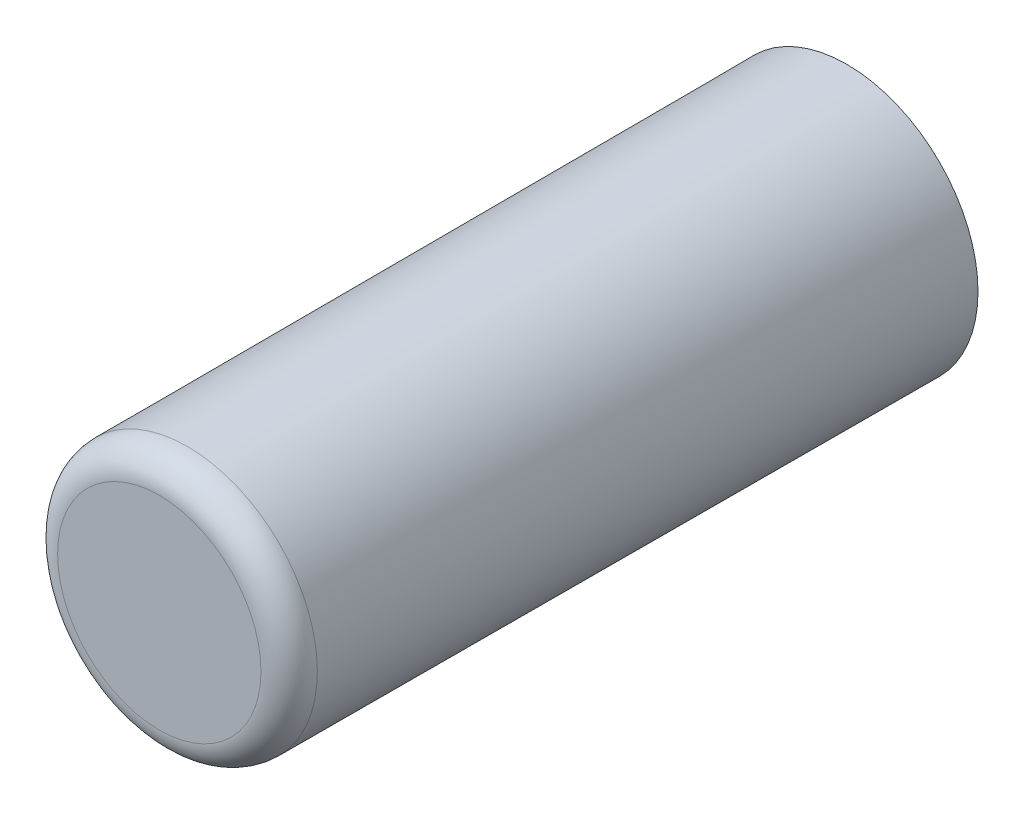
SolidWorks part; units mm, degrees
ref_plane "Front" through (0, 0, 0) normal (0, 0, 1) x (1, 0, 0)
ref_plane "Top" through (0, 0, 0) normal (0, 1, 0) x (1, 0, 0)
ref_plane "Right" through (0, 0, 0) normal (1, 0, 0) x (0, 0, -1)
sketch "Sketch1" plane through (0, 0, 0) normal (0, 1, 0) x (1, 0, 0)
  line L0 (0, 0) -> (0, -48.768) construction
  line L1 (0, -48.768) -> (9.2075, -48.768)
  line L2 (9.2075, -48.768) -> (9.3027, 0)
  line L3 (9.3027, 0) -> (8.382, 0)
  line L4 (8.382, 0) -> (8.382, -1.27)
  line L5 (8.382, -1.27) -> (6.604, -1.27)
  line L6 (6.604, -1.27) -> (6.604, 0)
  line L7 (6.604, 0) -> (2.8067, 0)
  line L8 (2.8067, 0) -> (2.8067, -4.572)
  line L9 (2.8067, -4.572) -> (0, -4.572)
  line L10 (0, -4.572) -> (0, -48.768)
  dimension "D1" = 18.6055
  dimension "D2" = 18.415
  dimension "D3" = 48.768
  dimension "D4" = 5.6134
  dimension "D5" = 4.572
  dimension "D6" = 13.208
  dimension "D7" = 1.27
  dimension "D8" = 1.778
  dimension "D9" = 0.9207
revolve "Revolve1" add sketch "Sketch1" angle 360 about L0
sketch "Sketch2" plane through (0, 0, 0) normal (1, 0, 0) x (0, 0, -1)
  line L0 (-1.27, -8.382) -> (-1.27, 8.382) construction
  line L1 (0, 6.604) -> (-1.27, 6.604) construction
  line L2 (0, 0) -> (-14.6658, 0) construction
  circle A0 centre (-0.381, 7.493) radius 0.889
  dimension "D1" = 1.778
revolve "Revolve2" add sketch "Sketch2" angle 360 about L2
fillet "Fillet1" radius 2 1 edges at (-9.2075, 0, 48.768)
